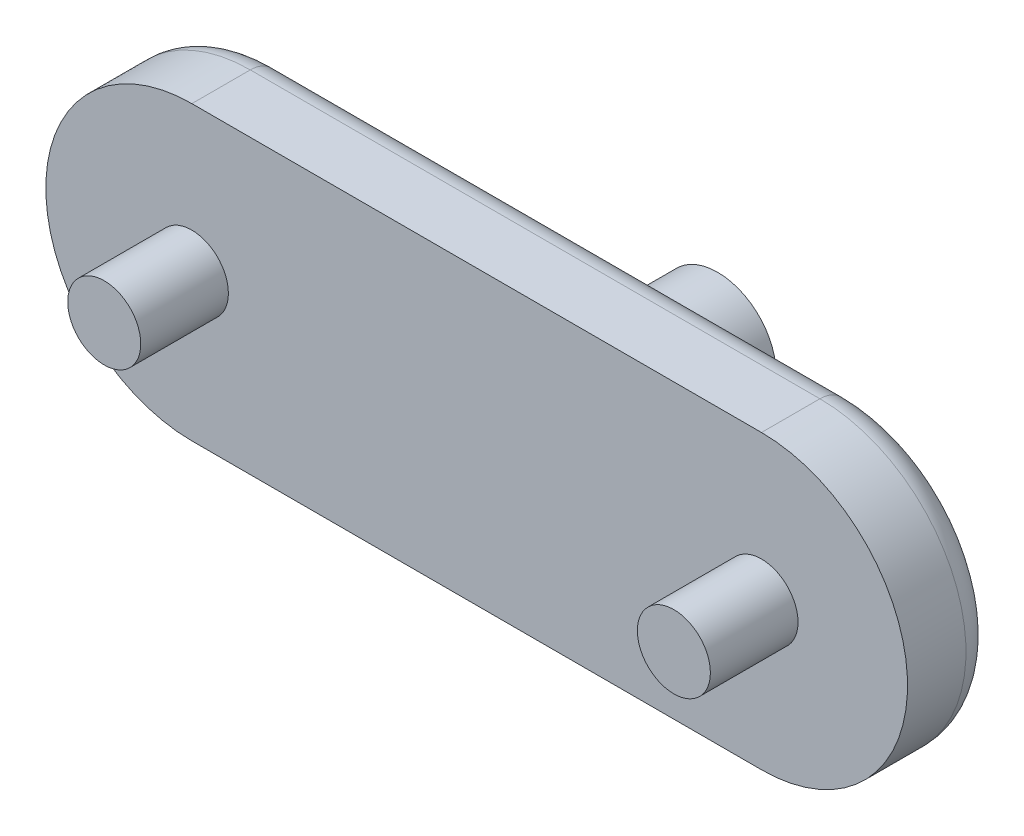
SolidWorks part; units mm, degrees
material "ABS PC"
ref_plane "Plan de face" through (0, 0, 0) normal (0, 0, 1) x (1, 0, 0)
ref_plane "Plan de dessus" through (0, 0, 0) normal (0, 1, 0) x (1, 0, 0)
ref_plane "Plan de droite" through (0, 0, 0) normal (1, 0, 0) x (0, 0, -1)
sketch "Esquisse1" plane through (0, 0, 0) normal (0, 0, 1) x (1, 0, 0)
  line L0 (0, 0) -> (-19.5, 0) construction
  line L1 (0, -5) -> (-19.5, -5)
  line L2 (0, 5) -> (-19.5, 5)
  arc A0 (0, -5) -> (0, 5) centre (0, 0) ccw
  arc A1 (-19.5, 5) -> (-19.5, -5) centre (-19.5, 0) ccw
  point P3 (-9.75, 0)
  dimension "D1" = 19.5
  dimension "D2" = 10
extrude "Boss.-Extru.1" add sketch "Esquisse1" along normal blind 3
sketch "Esquisse2" plane through (0, 0, 3) normal (0, 0, 1) x (1, 0, 0)
  circle A0 centre (-19.5, 0) radius 1.25
  circle A1 centre (0, 0) radius 1.25
  dimension "D1" = 2.5
  dimension "D2" = 2.5
extrude "Boss.-Extru.2" add sketch "Esquisse2" along normal blind 3 contours A0
sketch "Esquisse3" plane through (0, 0, 0) normal (0, 0, -1) x (-1, 0, 0)
  circle A0 centre (8.5, 0) radius 2
  point P2 (0, 0)
  point P3 (9.5445, 0)
  dimension "D1" = 4
  dimension "D2" = 8.5
extrude "Boss.-Extru.3" add sketch "Esquisse3" along normal blind 4 contours A0
fillet "Congé1" radius 1 4 edges at (5, 0, 0) (-9.75, -5, 0) (-24.5, 0, 0) (-9.75, 5, 0)
